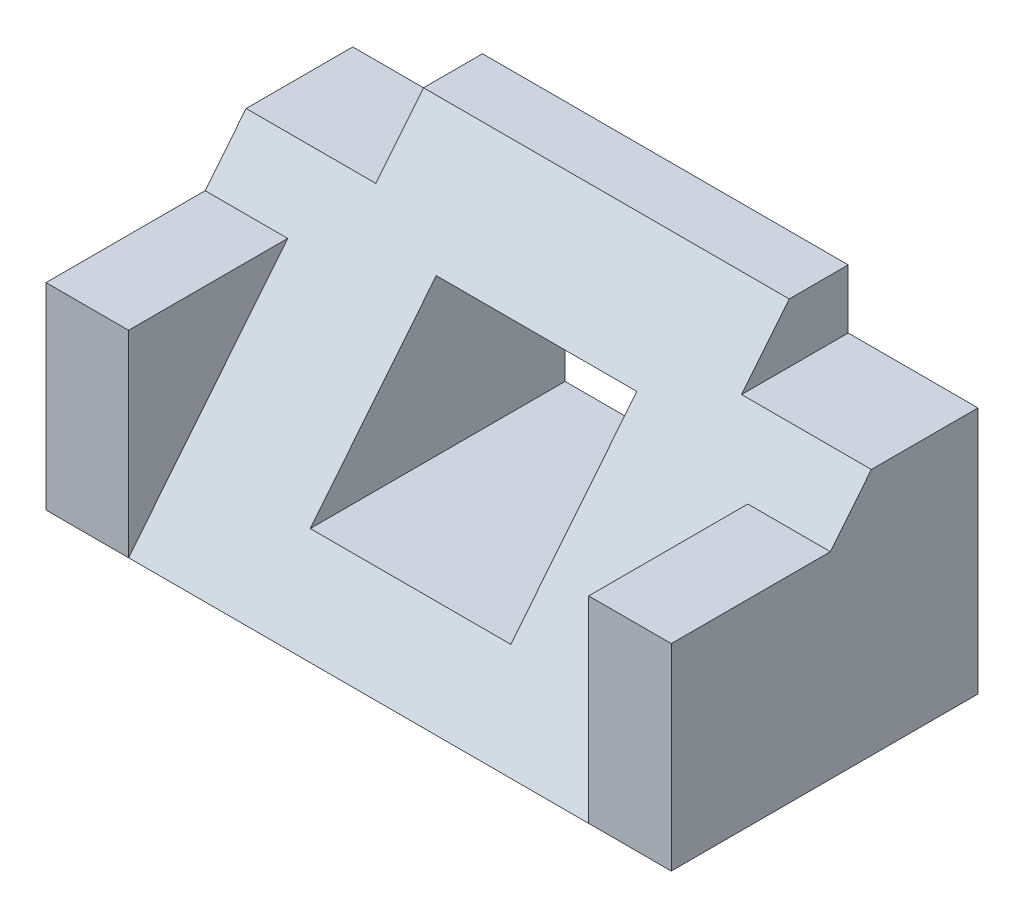
SolidWorks part; units mm, degrees
ref_plane "Plan de face" through (0, 0, 0) normal (0, 0, 1) x (1, 0, 0)
ref_plane "Plan de dessus" through (0, 0, 0) normal (0, 1, 0) x (1, 0, 0)
ref_plane "Plan de droite" through (0, 0, 0) normal (1, 0, 0) x (0, 0, -1)
sketch "Esquisse1" plane through (0, 0, 0) normal (1, 0, 0) x (0, 0, -1)
  line L1 (-13, -13) -> (13, -13)
  line L2 (-13, -13) -> (-13, 13)
  line L3 (-13, 13) -> (13, 13)
  line L4 (13, -13) -> (13, 13)
  line L5 (-13, -13) -> (13, 13) construction
  line L6 (-13, 13) -> (13, -13) construction
  point P0 (0, 0)
  dimension "D1" = 26
  dimension "D2" = 26
extrude "Boss.-Extru.1" add sketch "Esquisse1" along normal mid plane 53
sketch "Esquisse3" plane through (0, 0, 0) normal (1, 0, 0) x (0, 0, -1)
  line L0 (-13, -13) -> (8, 13)
  line L1 (13, 13) -> (-13, 13) construction
  line L2 (-13, -13) -> (-13, 13)
  line L3 (-13, 13) -> (8, 13)
  dimension "D1" = 5
extrude "Enlèv. mat.-Extru.1" cut sketch "Esquisse3" against normal mid plane 39
sketch "Esquisse4" plane through (0, 0, 13) normal (0, 0, 1) x (1, 0, 0)
  line L0 (26.5, 13) -> (26.5, -13) construction
  line L1 (26.5, 8) -> (15.5, 8)
  line L2 (26.5, 8) -> (26.5, 18)
  line L3 (26.5, 18) -> (15.5, 18)
  line L4 (15.5, 8) -> (15.5, 18)
  line L5 (26.5, 13) -> (19.5, 13) construction
  dimension "D1" = 10
  dimension "D2" = 11
  dimension "D3" = 5
extrude "Enlèv. mat.-Extru.2" cut sketch "Esquisse4" against normal through all
mirror "Symétrie1" about plane through (0, 0, 0) normal (1, 0, 0) of "Enlèv. mat.-Extru.2"
sketch "Esquisse5" plane through (26.5, 0, 0) normal (1, 0, 0) x (0, 0, -1)
  line L0 (-13, 3.7) -> (0.4885, 3.7)
  line L1 (0.4885, 3.7) -> (3.9615, 8)
  line L2 (3.9615, 8) -> (8, 13) construction
  line L3 (-13, 8) -> (-13, -13) construction
  line L4 (-13, 3.7) -> (-13, 8)
  line L5 (-13, 8) -> (3.9615, 8)
  dimension "D1" = 16.7
extrude "Enlèv. mat.-Extru.3" cut sketch "Esquisse5" against normal through all
sketch "Esquisse6" plane through (0, 1.222, 1.513) normal (0, 0.6283, 0.7779) x (1, 0, 0)
  line L0 (19.5, -5.29) -> (19.5, -18.2816) construction
  line L1 (-8.5, -11.2816) -> (8.5, -11.2816)
  line L2 (-8.5, -11.2816) -> (-8.5, 5.7184)
  line L3 (-8.5, 5.7184) -> (8.5, 5.7184)
  line L4 (8.5, -11.2816) -> (8.5, 5.7184)
  line L5 (-8.5, -11.2816) -> (8.5, 5.7184) construction
  line L6 (-8.5, 5.7184) -> (8.5, -11.2816) construction
  line L7 (-19.5, -18.2816) -> (19.5, -18.2816) construction
  point P0 (0, -2.7816)
  dimension "D1" = 17
  dimension "D2" = 17
  dimension "D3" = 11
  dimension "D4" = 7
extrude "Enlèv. mat.-Extru.4" cut sketch "Esquisse6" along direction (0, 0, -1) on the side against the normal through all
